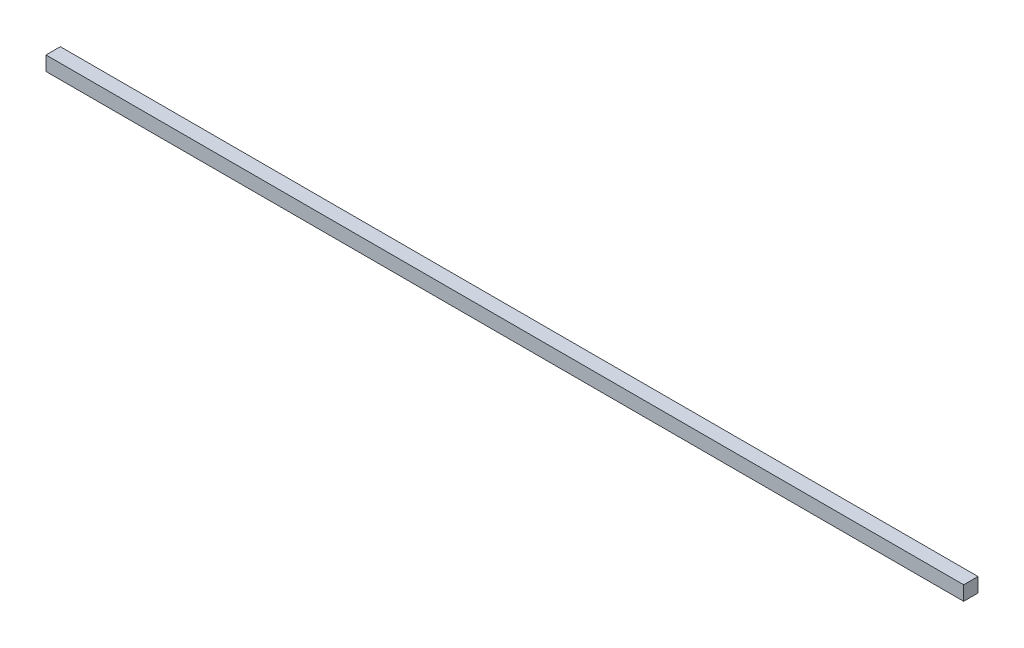
SolidWorks part; units mm, degrees
material "Pine"
ref_plane "Front Plane" through (0, 0, 0) normal (0, 0, 1) x (1, 0, 0)
ref_plane "Top Plane" through (0, 0, 0) normal (0, 1, 0) x (1, 0, 0)
ref_plane "Right Plane" through (0, 0, 0) normal (1, 0, 0) x (0, 0, -1)
sketch "Sketch1" plane through (0, 0, 0) normal (0, 0, 1) x (1, 0, 0)
  line L1 (-1219.2, 19.05) -> (1219.2, 19.05)
  line L2 (-1219.2, 19.05) -> (-1219.2, -19.05)
  line L3 (-1219.2, -19.05) -> (1219.2, -19.05)
  line L4 (1219.2, 19.05) -> (1219.2, -19.05)
  point P4 (0, 19.05)
  point P6 (1219.2, 0)
  dimension "D1" = 2438.4
  dimension "D2" = 38.1
extrude "Boss-Extrude1" add sketch "Sketch1" along normal blind 38.1
